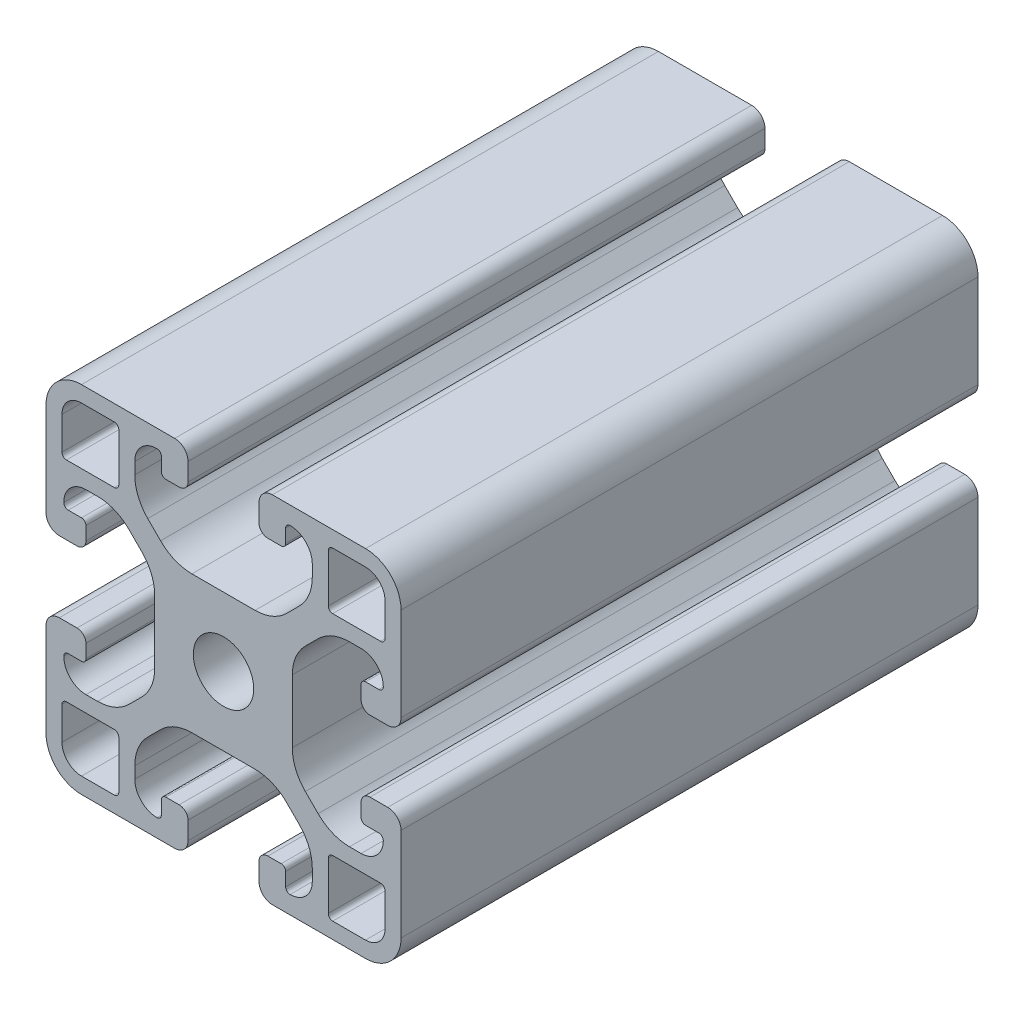
SolidWorks part; units mm, degrees
ref_plane "Plan de face" through (0, 0, 0) normal (0, 0, 1) x (1, 0, 0)
ref_plane "Plan de dessus" through (0, 0, 0) normal (0, 1, 0) x (1, 0, 0)
ref_plane "Plan de droite" through (0, 0, 0) normal (1, 0, 0) x (0, 0, -1)
ref_plane "Plan1" through (0, 0, -30) normal (0, 0, -1) x (-1, 0, 0)
sketch "Esquisse1" plane through (0, 0, -30) normal (0, 0, -1) x (-1, 0, 0)
  line L0 (-4.5, 15) -> (-4.5, 13.5)
  line L1 (-4, 13) -> (-2.5, 13)
  line L2 (-4.5, 10) -> (-5.8076, 10)
  line L3 (-9.3431, 11.4645) -> (-10.7855, 12.9069)
  line L4 (-12.25, 16.4424) -> (-12.25, 23.5576)
  line L5 (-10.7855, 27.0931) -> (-9.3431, 28.5355)
  line L6 (-5.8076, 30) -> (-4.5, 30)
  line L7 (-2.5, 27) -> (-4, 27)
  line L8 (-4.5, 26.5) -> (-4.5, 25)
  line L9 (-3.5, 24) -> (-1.5, 24)
  line L10 (0, 25.5) -> (0, 36)
  line L11 (-4, 40) -> (-14.5, 40)
  line L12 (-16, 38.5) -> (-16, 36.5)
  line L13 (-15, 35.5) -> (-13.5, 35.5)
  line L14 (-13, 36) -> (-13, 37.5)
  line L15 (-10, 35.5) -> (-10, 34.1924)
  line L16 (-11.4645, 30.6569) -> (-12.9069, 29.2145)
  line L17 (-16.4424, 27.75) -> (-23.5576, 27.75)
  line L18 (-27.0931, 29.2145) -> (-28.5355, 30.6569)
  line L19 (-30, 34.1924) -> (-30, 35.5)
  line L20 (-27, 37.5) -> (-27, 36)
  line L21 (-26.5, 35.5) -> (-25, 35.5)
  line L22 (-24, 36.5) -> (-24, 38.5)
  line L23 (-25.5, 40) -> (-36, 40)
  line L24 (-40, 36) -> (-40, 25.5)
  line L25 (-38.5, 24) -> (-36.5, 24)
  line L26 (-35.5, 25) -> (-35.5, 26.5)
  line L27 (-36, 27) -> (-37.5, 27)
  line L28 (-35.5, 30) -> (-34.1924, 30)
  line L29 (-30.6569, 28.5355) -> (-29.2145, 27.0931)
  line L30 (-27.75, 23.5576) -> (-27.75, 16.4424)
  line L31 (-29.2145, 12.9069) -> (-30.6569, 11.4645)
  line L32 (-34.1924, 10) -> (-35.5, 10)
  line L33 (-37.5, 13) -> (-36, 13)
  line L34 (-35.5, 13.5) -> (-35.5, 15)
  line L35 (-36.5, 16) -> (-38.5, 16)
  line L36 (-40, 14.5) -> (-40, 4)
  line L37 (-36, 0) -> (-25.5, 0)
  line L38 (-24, 1.5) -> (-24, 3.5)
  line L39 (-25, 4.5) -> (-26.5, 4.5)
  line L40 (-27, 4) -> (-27, 2.5)
  line L41 (-30, 4.5) -> (-30, 5.8076)
  line L42 (-28.5355, 9.3431) -> (-27.0931, 10.7855)
  line L43 (-23.5576, 12.25) -> (-16.4424, 12.25)
  line L44 (-12.9069, 10.7855) -> (-11.4645, 9.3431)
  line L45 (-10, 5.8076) -> (-10, 4.5)
  line L46 (-13, 2.5) -> (-13, 4)
  line L47 (-13.5, 4.5) -> (-15, 4.5)
  line L48 (-16, 3.5) -> (-16, 1.5)
  line L49 (-14.5, 0) -> (-4, 0)
  line L50 (0, 4) -> (0, 14.5)
  line L51 (-1.5, 16) -> (-3.5, 16)
  line L52 (-4, 1.8) -> (-7.7, 1.8)
  line L53 (-8.2, 2.3) -> (-8.2, 7.7)
  line L54 (-7.7, 8.2) -> (-2.3, 8.2)
  line L55 (-1.8, 7.7) -> (-1.8, 4)
  line L56 (-38.2, 4) -> (-38.2, 7.7)
  line L57 (-37.7, 8.2) -> (-32.3, 8.2)
  line L58 (-31.8, 7.7) -> (-31.8, 2.3)
  line L59 (-32.3, 1.8) -> (-36, 1.8)
  line L60 (-36, 38.2) -> (-32.3, 38.2)
  line L61 (-31.8, 37.7) -> (-31.8, 32.3)
  line L62 (-32.3, 31.8) -> (-37.7, 31.8)
  line L63 (-38.2, 32.3) -> (-38.2, 36)
  line L64 (-1.8, 36) -> (-1.8, 32.3)
  line L65 (-2.3, 31.8) -> (-7.7, 31.8)
  line L66 (-8.2, 32.3) -> (-8.2, 37.7)
  line L67 (-7.7, 38.2) -> (-4, 38.2)
  arc A0 (-4.5, 13.5) -> (-4, 13) centre (-4, 13.5) ccw
  arc A1 (-2.5, 13) -> (-2, 12.5) centre (-2.5, 12.5) cw
  arc A2 (-2, 12.5) -> (-4.5, 10) centre (-4.5, 12.5) cw
  arc A3 (-5.8076, 10) -> (-9.3431, 11.4645) centre (-5.8076, 15) cw
  arc A4 (-10.7855, 12.9069) -> (-12.25, 16.4424) centre (-7.25, 16.4424) cw
  arc A5 (-12.25, 23.5576) -> (-10.7855, 27.0931) centre (-7.25, 23.5576) cw
  arc A6 (-9.3431, 28.5355) -> (-5.8076, 30) centre (-5.8076, 25) cw
  arc A7 (-4.5, 30) -> (-2, 27.5) centre (-4.5, 27.5) cw
  arc A8 (-2, 27.5) -> (-2.5, 27) centre (-2.5, 27.5) cw
  arc A9 (-4, 27) -> (-4.5, 26.5) centre (-4, 26.5) ccw
  arc A10 (-4.5, 25) -> (-3.5, 24) centre (-3.5, 25) ccw
  arc A11 (-1.5, 24) -> (0, 25.5) centre (-1.5, 25.5) ccw
  arc A12 (0, 36) -> (-4, 40) centre (-4, 36) ccw
  arc A13 (-14.5, 40) -> (-16, 38.5) centre (-14.5, 38.5) ccw
  arc A14 (-16, 36.5) -> (-15, 35.5) centre (-15, 36.5) ccw
  arc A15 (-13.5, 35.5) -> (-13, 36) centre (-13.5, 36) ccw
  arc A16 (-13, 37.5) -> (-12.5, 38) centre (-12.5, 37.5) cw
  arc A17 (-12.5, 38) -> (-10, 35.5) centre (-12.5, 35.5) cw
  arc A18 (-10, 34.1924) -> (-11.4645, 30.6569) centre (-15, 34.1924) cw
  arc A19 (-12.9069, 29.2145) -> (-16.4424, 27.75) centre (-16.4424, 32.75) cw
  arc A20 (-23.5576, 27.75) -> (-27.0931, 29.2145) centre (-23.5576, 32.75) cw
  arc A21 (-28.5355, 30.6569) -> (-30, 34.1924) centre (-25, 34.1924) cw
  arc A22 (-30, 35.5) -> (-27.5, 38) centre (-27.5, 35.5) cw
  arc A23 (-27.5, 38) -> (-27, 37.5) centre (-27.5, 37.5) cw
  arc A24 (-27, 36) -> (-26.5, 35.5) centre (-26.5, 36) ccw
  arc A25 (-25, 35.5) -> (-24, 36.5) centre (-25, 36.5) ccw
  arc A26 (-24, 38.5) -> (-25.5, 40) centre (-25.5, 38.5) ccw
  arc A27 (-36, 40) -> (-40, 36) centre (-36, 36) ccw
  arc A28 (-40, 25.5) -> (-38.5, 24) centre (-38.5, 25.5) ccw
  arc A29 (-36.5, 24) -> (-35.5, 25) centre (-36.5, 25) ccw
  arc A30 (-35.5, 26.5) -> (-36, 27) centre (-36, 26.5) ccw
  arc A31 (-37.5, 27) -> (-38, 27.5) centre (-37.5, 27.5) cw
  arc A32 (-38, 27.5) -> (-35.5, 30) centre (-35.5, 27.5) cw
  arc A33 (-34.1924, 30) -> (-30.6569, 28.5355) centre (-34.1924, 25) cw
  arc A34 (-29.2145, 27.0931) -> (-27.75, 23.5576) centre (-32.75, 23.5576) cw
  arc A35 (-27.75, 16.4424) -> (-29.2145, 12.9069) centre (-32.75, 16.4424) cw
  arc A36 (-30.6569, 11.4645) -> (-34.1924, 10) centre (-34.1924, 15) cw
  arc A37 (-35.5, 10) -> (-38, 12.5) centre (-35.5, 12.5) cw
  arc A38 (-38, 12.5) -> (-37.5, 13) centre (-37.5, 12.5) cw
  arc A39 (-36, 13) -> (-35.5, 13.5) centre (-36, 13.5) ccw
  arc A40 (-35.5, 15) -> (-36.5, 16) centre (-36.5, 15) ccw
  arc A41 (-38.5, 16) -> (-40, 14.5) centre (-38.5, 14.5) ccw
  arc A42 (-40, 4) -> (-36, 0) centre (-36, 4) ccw
  arc A43 (-25.5, 0) -> (-24, 1.5) centre (-25.5, 1.5) ccw
  arc A44 (-24, 3.5) -> (-25, 4.5) centre (-25, 3.5) ccw
  arc A45 (-26.5, 4.5) -> (-27, 4) centre (-26.5, 4) ccw
  arc A46 (-27, 2.5) -> (-27.5, 2) centre (-27.5, 2.5) cw
  arc A47 (-27.5, 2) -> (-30, 4.5) centre (-27.5, 4.5) cw
  arc A48 (-30, 5.8076) -> (-28.5355, 9.3431) centre (-25, 5.8076) cw
  arc A49 (-27.0931, 10.7855) -> (-23.5576, 12.25) centre (-23.5576, 7.25) cw
  arc A50 (-16.4424, 12.25) -> (-12.9069, 10.7855) centre (-16.4424, 7.25) cw
  arc A51 (-11.4645, 9.3431) -> (-10, 5.8076) centre (-15, 5.8076) cw
  arc A52 (-10, 4.5) -> (-12.5, 2) centre (-12.5, 4.5) cw
  arc A53 (-12.5, 2) -> (-13, 2.5) centre (-12.5, 2.5) cw
  arc A54 (-13, 4) -> (-13.5, 4.5) centre (-13.5, 4) ccw
  arc A55 (-15, 4.5) -> (-16, 3.5) centre (-15, 3.5) ccw
  arc A56 (-16, 1.5) -> (-14.5, 0) centre (-14.5, 1.5) ccw
  arc A57 (-4, 0) -> (0, 4) centre (-4, 4) ccw
  arc A58 (0, 14.5) -> (-1.5, 16) centre (-1.5, 14.5) ccw
  arc A59 (-3.5, 16) -> (-4.5, 15) centre (-3.5, 15) ccw
  circle A60 centre (-20, 20) radius 3.4
  arc A61 (-1.8, 4) -> (-4, 1.8) centre (-4, 4) cw
  arc A62 (-7.7, 1.8) -> (-8.2, 2.3) centre (-7.7, 2.3) cw
  arc A63 (-8.2, 7.7) -> (-7.7, 8.2) centre (-7.7, 7.7) cw
  arc A64 (-2.3, 8.2) -> (-1.8, 7.7) centre (-2.3, 7.7) cw
  arc A65 (-36, 1.8) -> (-38.2, 4) centre (-36, 4) cw
  arc A66 (-38.2, 7.7) -> (-37.7, 8.2) centre (-37.7, 7.7) cw
  arc A67 (-32.3, 8.2) -> (-31.8, 7.7) centre (-32.3, 7.7) cw
  arc A68 (-31.8, 2.3) -> (-32.3, 1.8) centre (-32.3, 2.3) cw
  arc A69 (-38.2, 36) -> (-36, 38.2) centre (-36, 36) cw
  arc A70 (-32.3, 38.2) -> (-31.8, 37.7) centre (-32.3, 37.7) cw
  arc A71 (-31.8, 32.3) -> (-32.3, 31.8) centre (-32.3, 32.3) cw
  arc A72 (-37.7, 31.8) -> (-38.2, 32.3) centre (-37.7, 32.3) cw
  arc A73 (-4, 38.2) -> (-1.8, 36) centre (-4, 36) cw
  arc A74 (-1.8, 32.3) -> (-2.3, 31.8) centre (-2.3, 32.3) cw
  arc A75 (-7.7, 31.8) -> (-8.2, 32.3) centre (-7.7, 32.3) cw
  arc A76 (-8.2, 37.7) -> (-7.7, 38.2) centre (-7.7, 37.7) cw
extrude "Boss.-Extru.1" add sketch "Esquisse1" against normal blind 65
